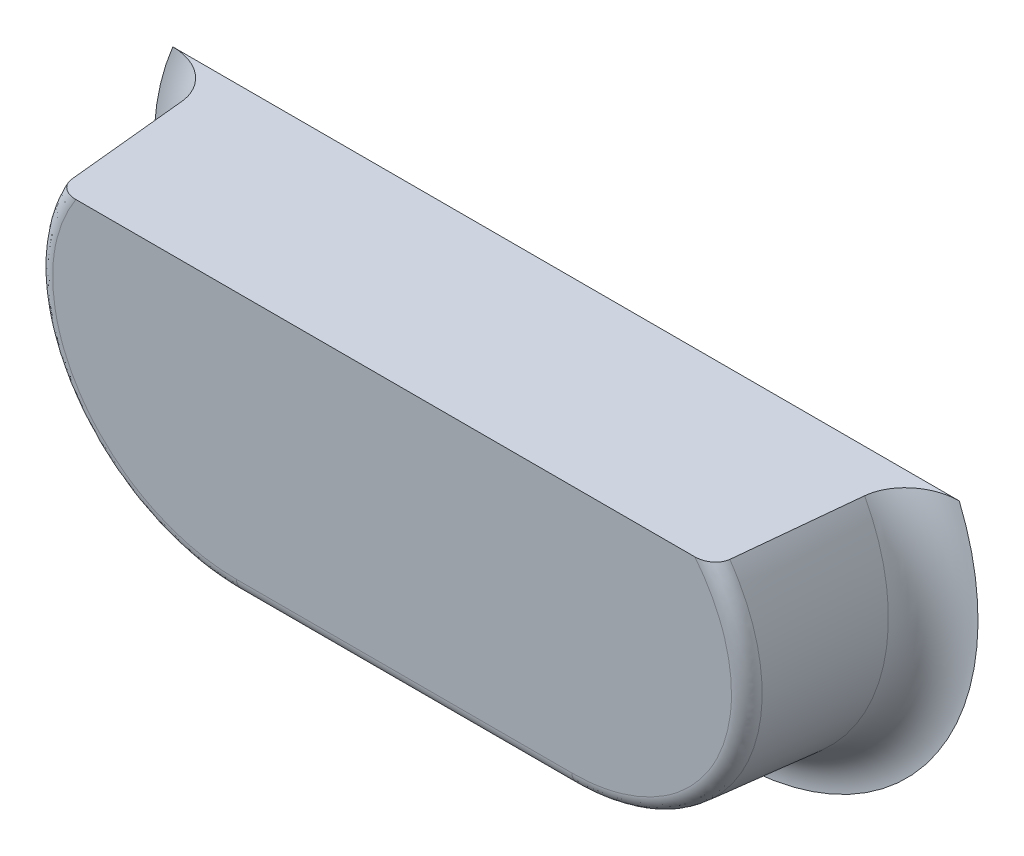
SolidWorks part; units mm, degrees
ref_plane "Front Plane" through (0, 0, 0) normal (0, 0, 1) x (1, 0, 0)
ref_plane "Top Plane" through (0, 0, 0) normal (0, 1, 0) x (1, 0, 0)
ref_plane "Right Plane" through (0, 0, 0) normal (1, 0, 0) x (0, 0, -1)
other "Configuration Table"
sketch "Sketch1" plane through (0, 0, 0) normal (0, 0, 1) x (1, 0, 0)
  line L0 (21.4501, 8.8169) -> (46.4501, 8.8169)
  line L2 (46.4501, 38.8169) -> (21.4501, 38.8169)
  arc A0 (21.4501, 38.8169) -> (21.4501, 8.8169) centre (21.4501, 23.8169) ccw
  arc A1 (46.4501, 8.8169) -> (46.4501, 38.8169) centre (46.4501, 23.8169) ccw
extrude "Boss-Extrude1" add sketch "Sketch1" along normal blind 12 draft 5
sketch "Sketch2" plane through (0, 0, 0) normal (0, 0, -1) x (-1, 0, 0)
  line L0 (-21.4501, 8.8169) -> (-46.4501, 8.8169) construction
  line L1 (-64.8327, 30.8169) -> (0.8309, 30.8169)
  line L2 (-64.8327, 30.8169) -> (-64.8327, 44.1774)
  line L3 (-64.8327, 44.1774) -> (0.8309, 44.1774)
  line L4 (0.8309, 30.8169) -> (0.8309, 44.1774)
  dimension "D1" = 22
extrude "Cut-Extrude1" cut sketch "Sketch2" against normal through all
sketch "Sketch3" plane through (0, 0, 0) normal (0, 0, -1) x (-1, 0, 0)
  line L1 (-68.5375, 0.8067) -> (3.5951, 0.8067)
  line L2 (-68.5375, 0.8067) -> (-68.5375, 38.0078)
  line L3 (-68.5375, 38.0078) -> (3.5951, 38.0078)
  line L4 (3.5951, 0.8067) -> (3.5951, 38.0078)
extrude "Boss-Extrude2" add sketch "Sketch3" along normal blind 10
fillet "Fillet1" radius 3.5 3 edges at (59.2954, 16.071, 0) (33.9501, 8.8169, 0) (8.6049, 16.071, 0)
sketch "Sketch4" plane through (0, 0.8067, 0) normal (0, -1, 0) x (1, 0, 0)
  line L1 (-3.5951, 0) -> (77.6552, 0)
  line L2 (-3.5951, 0) -> (-3.5951, -16.6186)
  line L3 (-3.5951, -16.6186) -> (77.6552, -16.6186)
  line L4 (77.6552, 0) -> (77.6552, -16.6186)
extrude "Cut-Extrude2" cut sketch "Sketch4" against normal through all
ref_plane "Plane1" through (0, 9.8668, 0) normal (0, 1, 0) x (1, 0, 0)
draft "Draft2" type of draft neutral plane draft angle 4 neutral plane "Plane1" faces to draft 1 face at (33.9501, 18.5981, 12) neutral plane through (0, 9.8668, 0) neutral plane normal (0, 1, 0) reverse direction yes parameters "D1"=4
fillet "Fillet3" radius 1.2 3 edges at (58.5015, 16.876, 12.4901) (33.9501, 9.8668, 12) (9.3988, 16.876, 12.4901)
